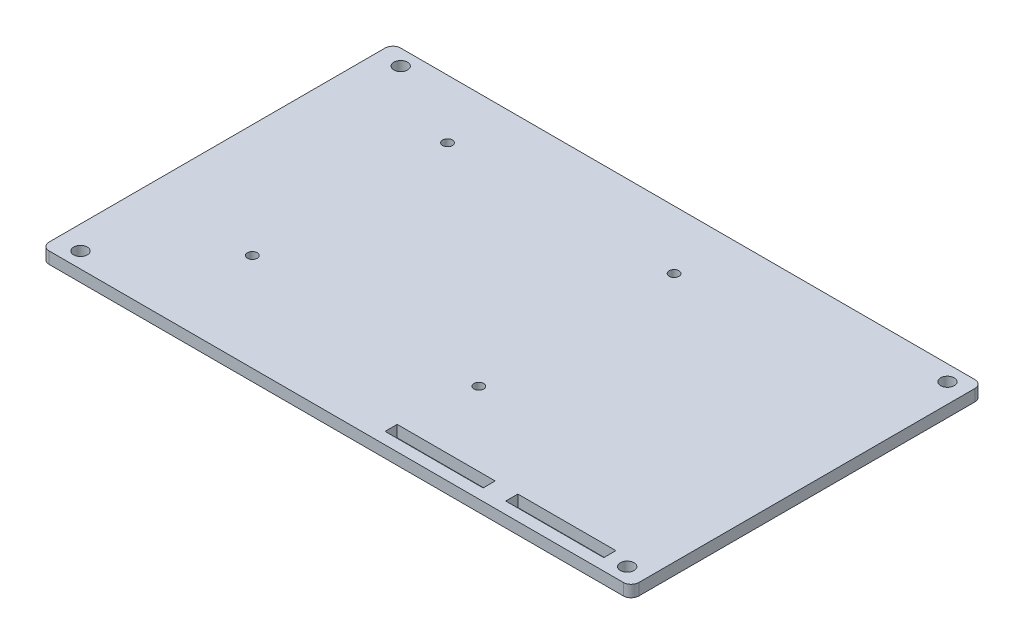
SolidWorks part; units mm, degrees
ref_plane "Front Plane" through (0, 0, 0) normal (0, 0, 1) x (1, 0, 0)
ref_plane "Top Plane" through (0, 0, 0) normal (0, 1, 0) x (1, 0, 0)
ref_plane "Right Plane" through (0, 0, 0) normal (1, 0, 0) x (0, 0, -1)
sketch "Sketch1" plane through (0, 0, 0) normal (0, 1, 0) x (1, 0, 0)
  line L1 (0, 0) -> (151, 0)
  line L2 (0, 0) -> (0, 90)
  line L3 (0, 90) -> (151, 90)
  line L4 (151, 0) -> (151, 90)
  dimension "D1" = 151
  dimension "D2" = 90
extrude "Boss-Extrude1" add sketch "Sketch1" along normal blind 3
sketch "Sketch2" plane through (0, 3, 0) normal (0, 1, 0) x (1, 0, 0)
  line L0 (151, 0) -> (151, 90) construction
  line L1 (151, 90) -> (0, 90) construction
  line L2 (0, 0) -> (151, 0) construction
  line L3 (0, 90) -> (0, 0) construction
  circle A0 centre (146, 86) radius 1.75
  circle A1 centre (146, 4) radius 1.75
  circle A2 centre (6, 86) radius 1.75
  circle A3 centre (6, 4) radius 1.75
  dimension "D1" = 3.5
  dimension "D2" = 5
  dimension "D3" = 4
  dimension "D4" = 3.5
  dimension "D5" = 5
  dimension "D6" = 4
  dimension "D7" = 4
  dimension "D8" = 6
  dimension "D9" = 3.5
  dimension "D10" = 3.5
  dimension "D11" = 6
  dimension "D12" = 4
extrude "Cut-Extrude1" cut sketch "Sketch2" against normal through all
fillet "Fillet1" radius 2 4 edges at (151, 1.5, -90) (151, 1.5, 0) (0, 1.5, 0) (0, 1.5, -90)
sketch "Sketch3" plane through (0, 3, 0) normal (0, 1, 0) x (1, 0, 0)
  line L0 (149, 90) -> (2, 90) construction
  line L1 (5, 78) -> (90, 78) construction
  line L2 (5, 78) -> (5, 22) construction
  line L3 (5, 22) -> (90, 22) construction
  line L4 (90, 78) -> (90, 22) construction
  line L5 (0, 88) -> (0, 2) construction
  circle A0 centre (87, 75) radius 1.25
  circle A1 centre (29, 75) radius 1.25
  circle A2 centre (87, 25) radius 1.25
  circle A3 centre (29, 25) radius 1.25
  point P4 (48.7324, 46.7086)
  dimension "D5" = 2.5
  dimension "D6" = 3
  dimension "D7" = 3
  dimension "D8" = 2.5
  dimension "D9" = 3
  dimension "D10" = 58
  dimension "D11" = 2.5
  dimension "D12" = 3
  dimension "D13" = 3
  dimension "D14" = 3
  dimension "D15" = 58
  dimension "D16" = 2.5
  dimension "D1" = 85
  dimension "D2" = 56
  dimension "D3" = 12
  dimension "D4" = 5
extrude "Cut-Extrude2" cut sketch "Sketch3" against normal through all
sketch "Sketch4" plane through (0, 3, 0) normal (0, 1, 0) x (1, 0, 0)
  line L0 (85, 3) -> (141, 3) construction
  line L1 (151, 2) -> (151, 88) construction
  line L2 (2, 0) -> (149, 0) construction
  line L4 (85, 3) -> (110.1, 3)
  line L5 (85, 3) -> (85, 6.1)
  line L6 (85, 6.1) -> (110.1, 6.1)
  line L7 (110.1, 3) -> (110.1, 6.1)
  line L8 (141, 3) -> (115.9, 3)
  line L9 (141, 3) -> (141, 6.1)
  line L10 (141, 6.1) -> (115.9, 6.1)
  line L11 (115.9, 3) -> (115.9, 6.1)
  dimension "D1" = 56
  dimension "D2" = 10
  dimension "D3" = 3
  dimension "D4" = 3.1
  dimension "D5" = 25.1
  dimension "D6" = 25.1
  dimension "D7" = 3.1
extrude "Cut-Extrude3" cut sketch "Sketch4" against normal through all and the other way through all
